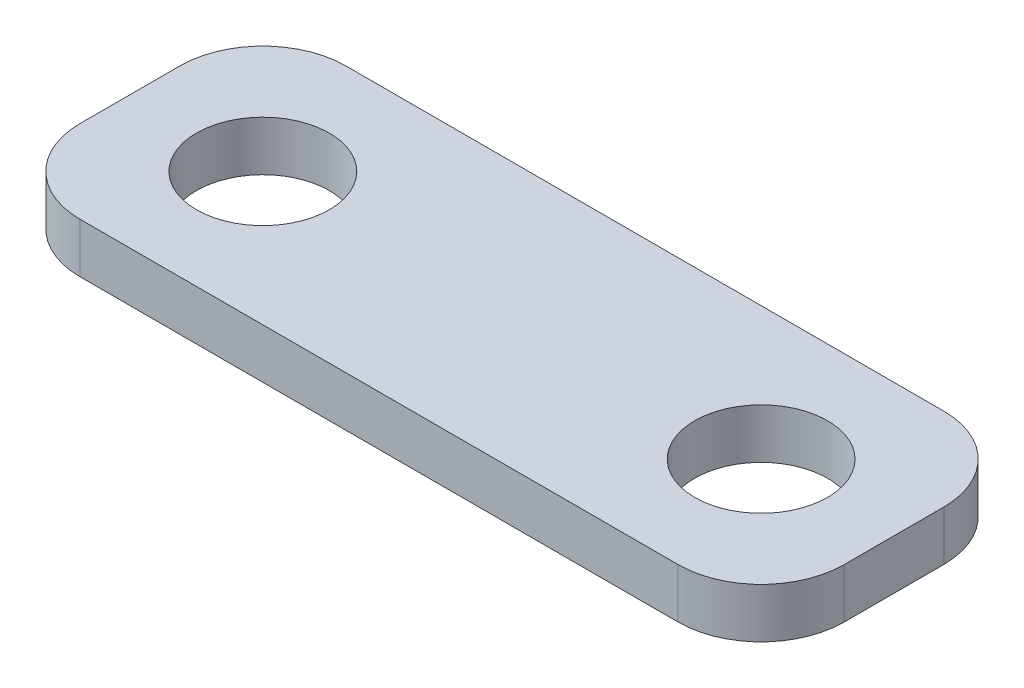
SolidWorks part; units mm, degrees
material "Plain Carbon Steel"
ref_plane "Front Plane" through (0, 0, 0) normal (0, 0, 1) x (1, 0, 0)
ref_plane "Top Plane" through (0, 0, 0) normal (0, 1, 0) x (1, 0, 0)
ref_plane "Right Plane" through (0, 0, 0) normal (1, 0, 0) x (0, 0, -1)
sketch "Sketch1" plane through (0, 0, 0) normal (0, 1, 0) x (1, 0, 0)
  line L1 (-23, 8) -> (23, 8)
  line L2 (-23, 8) -> (-23, -8)
  line L3 (-23, -8) -> (23, -8)
  line L4 (23, 8) -> (23, -8)
  line L5 (-23, 8) -> (23, -8) construction
  line L6 (-23, -8) -> (23, 8) construction
  circle A0 centre (-15, 0) radius 4
  circle A1 centre (15, 0) radius 4
  point P5 (0, 0)
  dimension "D3" = 8
  dimension "D4" = 8
  dimension "D6" = 8
  dimension "D1" = 30
  dimension "D2" = 15
  dimension "D5" = 8
extrude "Boss-Extrude1" add sketch "Sketch1" along normal blind 3
fillet "Fillet1" radius 5 4 edges at (-23, 1.5, 8) (-23, 1.5, -8) (23, 1.5, -8) (23, 1.5, 8)
